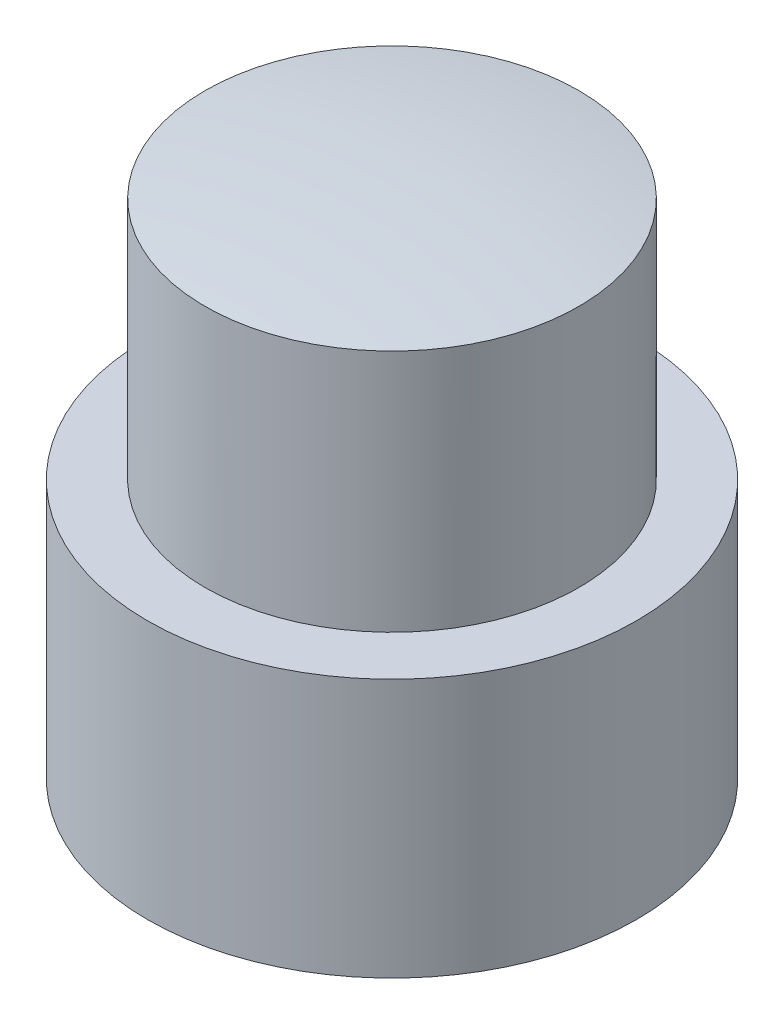
SolidWorks part; units mm, degrees
material "Printed PLA"
ref_plane "Front Plane" through (0, 0, 0) normal (0, 0, 1) x (1, 0, 0)
ref_plane "Top Plane" through (0, 0, 0) normal (0, 1, 0) x (1, 0, 0)
ref_plane "Right Plane" through (0, 0, 0) normal (1, 0, 0) x (0, 0, -1)
sketch "Sketch1" plane through (0, 0, 0) normal (0, 0, 1) x (1, 0, 0)
  line L0 (-1.75, 0) -> (-1.75, 2)
  line L1 (-1.75, 2) -> (0, 2)
  line L2 (0, 2) -> (0, 9) construction
  line L3 (0, 2) -> (0, 9)
  line L4 (-3.25, 8.7342) -> (-3.25, 4.5)
  line L5 (-3.25, 4.5) -> (-4.25, 4.5)
  line L6 (-4.25, 4.5) -> (-4.25, 0)
  line L7 (-4.25, 0) -> (-1.75, 0)
  arc A0 (0, 9) -> (-3.25, 8.7342) centre (0, -11) ccw
  dimension "D7" = 20
  dimension "D1" = 6.5
  dimension "D2" = 3.5
  dimension "D3" = 4.5
  dimension "D4" = 2
  dimension "D5" = 9
  dimension "D6" = 8.5
revolve "Revolve1" add sketch "Sketch1" angle 360 about L2
